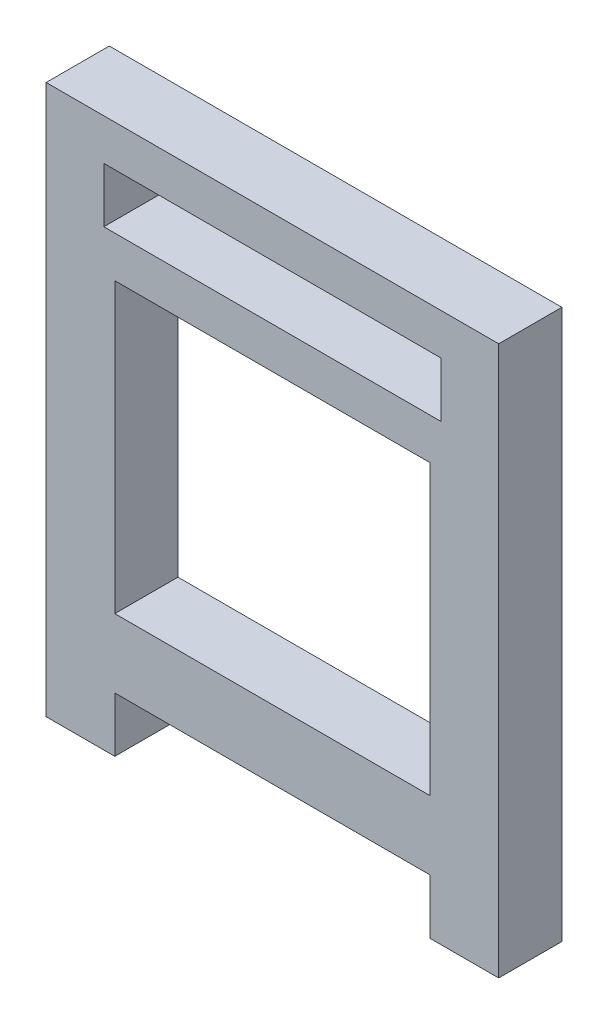
SolidWorks part; units mm, degrees
ref_plane "Front Plane" through (0, 0, 0) normal (0, 0, 1) x (1, 0, 0)
ref_plane "Top Plane" through (0, 0, 0) normal (0, 1, 0) x (1, 0, 0)
ref_plane "Right Plane" through (0, 0, 0) normal (1, 0, 0) x (0, 0, -1)
sketch "Sketch1" plane through (0, 0, 0) normal (0, 0, 1) x (1, 0, 0)
  line L0 (0, 0) -> (0, -2)
  line L1 (2.5, 0) -> (13.98, 0)
  line L2 (0, 0) -> (0, 18)
  line L3 (0, 18) -> (16.48, 18)
  line L4 (16.48, 0) -> (16.48, 18)
  line L5 (0, -2) -> (2.5, -2)
  line L6 (2.5, -2) -> (2.5, 0)
  line L7 (16.48, 0) -> (16.48, -2)
  line L8 (16.48, -2) -> (13.98, -2)
  line L9 (13.98, -2) -> (13.98, 0)
  line L12 (2.5, 2.5) -> (13.98, 2.5)
  line L13 (2.5, 2.5) -> (2.5, 13)
  line L14 (2.5, 13) -> (13.98, 13)
  line L15 (13.98, 2.5) -> (13.98, 13)
  line L16 (2.1, 14.5) -> (14.38, 14.5)
  line L17 (2.1, 14.5) -> (2.1, 16.5)
  line L18 (2.1, 16.5) -> (14.38, 16.5)
  line L19 (14.38, 14.5) -> (14.38, 16.5)
  point P19 (2.1, 15.5)
  dimension "D1" = 18
  dimension "D2" = 2.5
  dimension "D3" = 2.5
  dimension "D4" = 2
  dimension "D5" = 2
  dimension "D6" = 2.1
  dimension "D7" = 2.5
  dimension "D8" = 10.5
  dimension "D9" = 2
  dimension "D10" = 1.5
  dimension "D11" = 2.1
  dimension "D12" = 11.48
extrude "Boss-Extrude1" add sketch "Sketch1" along normal blind 2.3
